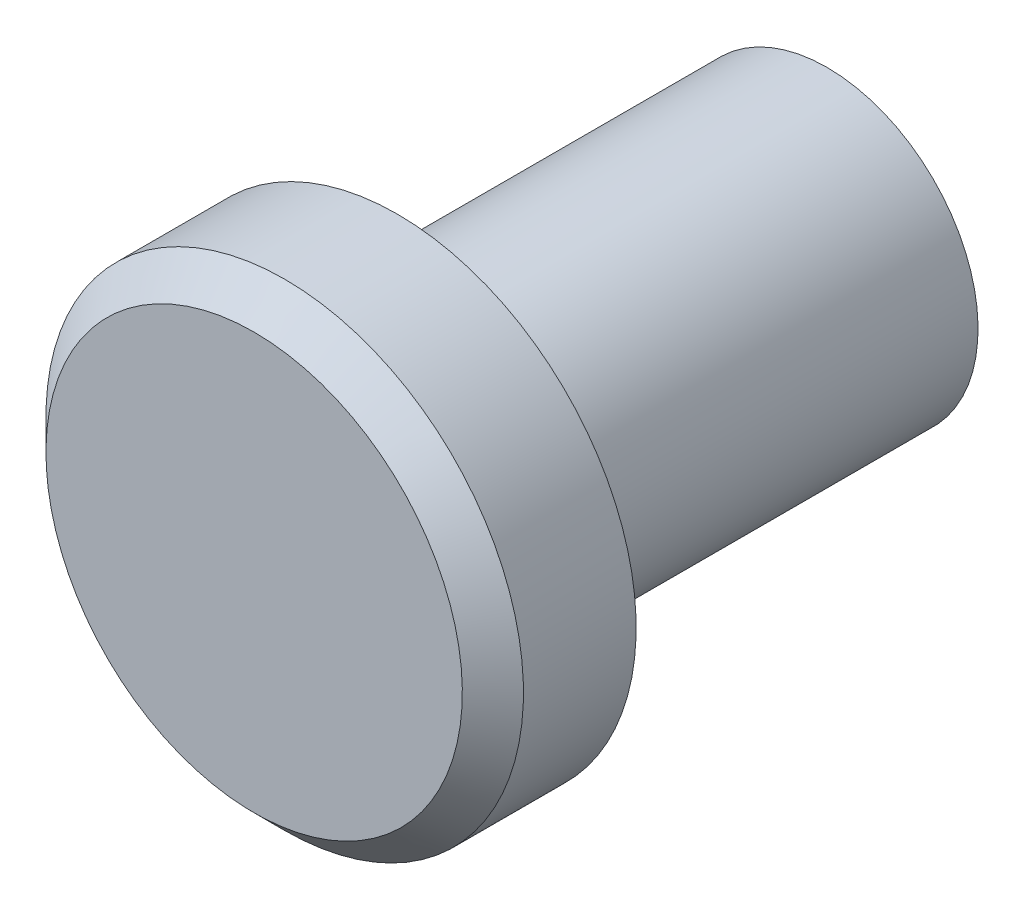
SolidWorks part; units mm, degrees
ref_plane "Front Plane" through (0, 0, 0) normal (0, 0, 1) x (1, 0, 0)
ref_plane "Top Plane" through (0, 0, 0) normal (0, 1, 0) x (1, 0, 0)
ref_plane "Right Plane" through (0, 0, 0) normal (1, 0, 0) x (0, 0, -1)
sketch "Sketch1" plane through (0, 0, 0) normal (1, 0, 0) x (0, 0, -1)
  line L0 (0, 0) -> (0, 6.35)
  line L1 (0, 6.35) -> (3.81, 6.35)
  line L2 (3.81, 6.35) -> (3.81, 4.0132)
  line L3 (3.81, 4.0132) -> (15.24, 4.0132)
  line L4 (15.24, 4.0132) -> (15.24, 2.921)
  line L5 (15.24, 2.921) -> (4.445, 2.921)
  line L6 (4.445, 2.921) -> (1.524, 0)
  line L7 (1.524, 0) -> (0, 0)
  point P3 (15.24, 3.4671)
  dimension "D1" = 6.35
  dimension "D2" = 3.81
  dimension "D3" = 45
  dimension "D4" = 2.921
  dimension "D5" = 4.0132
  dimension "D6" = 15.24
  dimension "D7" = 10.795
revolve "Revolve2" add sketch "Sketch1" angle 360 about L7
chamfer "Chamfer1" distance 0.8128 angle 45 2 edges at (0, 6.35, 0) (0, 2.921, -15.24)
